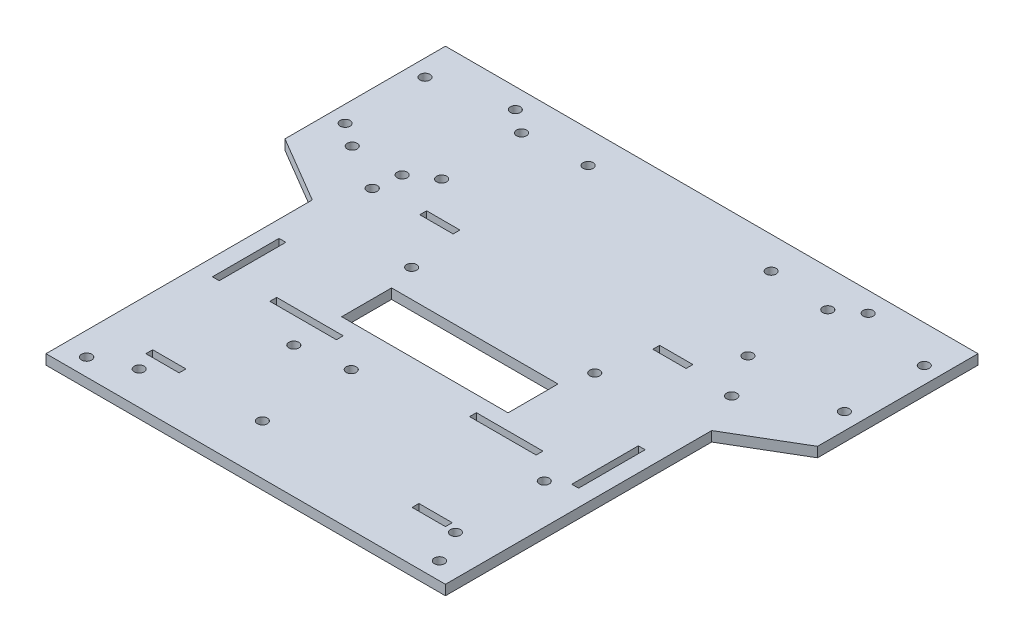
SolidWorks part; units mm, degrees
ref_plane "Front Plane" through (0, 0, 0) normal (0, 0, 1) x (1, 0, 0)
ref_plane "Top Plane" through (0, 0, 0) normal (0, 1, 0) x (1, 0, 0)
ref_plane "Right Plane" through (0, 0, 0) normal (1, 0, 0) x (0, 0, -1)
sketch "Sketch1" plane through (0, 0, 0) normal (0, 1, 0) x (1, 0, 0)
  line L0 (-60, 10) -> (-80, 21.7918)
  line L1 (60, -70) -> (-60, -70)
  line L2 (60, -70) -> (60, 70)
  line L3 (60, 70) -> (-60, 70)
  line L4 (-60, -70) -> (-60, 70)
  line L5 (60, -70) -> (-60, 70) construction
  line L6 (60, 70) -> (-60, -70) construction
  line L7 (-80, 21.7918) -> (-80, 70)
  line L8 (-80, 70) -> (-60, 70)
  line L9 (0, 0) -> (0, 70) construction
  line L10 (60, 10) -> (80, 21.7918)
  line L11 (80, 70) -> (60, 70)
  line L12 (80, 21.7918) -> (80, 70)
  point P0 (0, 0)
  dimension "D1" = 140
  dimension "D2" = 120
  dimension "D3" = 20
  dimension "D4" = 30.523
  dimension "D5" = 60
extrude "Boss-Extrude1" add sketch "Sketch1" along normal blind 3 contours L4 L1 L2 L3 | L8 L7 L0 L4 | L10 L12 L11 L2
sketch "Sketch2" plane through (0, 3, 0) normal (0, 1, 0) x (1, 0, 0)
  line L0 (60, -70) -> (60, 10) construction
  line L1 (-60, -70) -> (-60, 10) construction
  line L3 (60, -70) -> (-60, -70) construction
  circle A0 centre (-42, -60) radius 1.5
  circle A1 centre (-25, -30.5551) radius 1.5
  circle A2 centre (-10, -55) radius 1.5
  circle A3 centre (48, -55) radius 1.5
  circle A4 centre (-10, -28.3) radius 1.5
  circle A5 centre (48, -28.3) radius 1.5
  dimension "D1" = 3
  dimension "D2" = 34
  dimension "D3" = 10
  dimension "D4" = 3
  dimension "D6" = 3
  dimension "D9" = 15
  dimension "D7" = 3
  dimension "D11" = 12
  dimension "D12" = 3
  dimension "D13" = 3
  dimension "D5" = 17
  dimension "D8" = 58
  dimension "D10" = 15
  dimension "D14" = 26.7
  dimension "D15" = 26.7
  dimension "D16" = 58
  dimension "D17" = 12
  dimension "D18" = 18
extrude "Cut-Extrude1" cut sketch "Sketch2" against normal through all
sketch "Sketch3" plane through (0, 3, 0) normal (0, 1, 0) x (1, 0, 0)
  line L0 (-0.0296, 57.8856) -> (-0.0296, -0.1144) construction
  line L1 (-30.0296, 33.8856) -> (29.9704, 33.8856) construction
  line L4 (-80, 21.7918) -> (-80, 70) construction
  line L6 (-80, 21.7918) -> (-80, 70) construction
  line L7 (80, 70) -> (-80, 70) construction
  line L8 (-60, 10) -> (-60, 70) construction
  line L9 (60, 10) -> (60, 70) construction
  circle A0 centre (-27.5296, 60.3856) radius 1.5
  circle A1 centre (-27.5296, 7.3856) radius 1.5
  circle A2 centre (27.4704, 7.3856) radius 1.5
  circle A3 centre (27.4704, 60.3856) radius 1.5
  point P16 (-80, 45.8959)
  dimension "D1" = 52.4704
  dimension "D2" = 36.1144
  dimension "D3" = 3
  dimension "D4" = 79.9704
  dimension "D5" = 26.5
extrude "Cut-Extrude3" cut sketch "Sketch3" against normal through all
sketch "Sketch4" plane through (0, 3, 0) normal (0, 1, 0) x (1, 0, 0)
  line L0 (-60.5, 58.8639) -> (-60.5, 32.8639) construction
  line L1 (-80, 21.7918) -> (-80, 70) construction
  line L2 (80, 70) -> (-80, 70) construction
  line L3 (0, 0) -> (0, 70) construction
  circle A0 centre (-75, 34.8639) radius 1.5
  circle A1 centre (-75, 58.8639) radius 1.5
  circle A2 centre (-46, 34.8639) radius 1.5
  circle A3 centre (-46, 58.8639) radius 1.5
  circle A4 centre (46, 58.8639) radius 1.5
  circle A5 centre (46, 34.8639) radius 1.5
  circle A6 centre (75, 34.8639) radius 1.5
  circle A7 centre (75, 58.8639) radius 1.5
  dimension "D1" = 3
  dimension "D2" = 3
  dimension "D5" = 5
  dimension "D6" = 11.1361
  dimension "D7" = 5
  dimension "D3" = 24
  dimension "D4" = 14.5
extrude "Cut-Extrude4" cut sketch "Sketch4" against normal through all
sketch "Sketch5" plane through (0, 3, 0) normal (0, 1, 0) x (1, 0, 0)
  line L0 (80, 70) -> (-80, 70) construction
  line L1 (-80, 21.7918) -> (-80, 70) construction
  circle A0 centre (-68, 30) radius 1.5
  circle A1 centre (-53, 30) radius 1.5
  dimension "D1" = 3
  dimension "D2" = 3
  dimension "D3" = 40
  dimension "D4" = 40
  dimension "D6" = 12
  dimension "D5" = 15
extrude "Cut-Extrude5" cut sketch "Sketch5" against normal blind 3
sketch "Sketch6" plane through (0, 3, 0) normal (0, 1, 0) x (1, 0, 0)
  line L0 (60, -70) -> (-60, -70) construction
  line L1 (-45, -52.95) -> (-35, -52.95)
  line L2 (-45, -52.95) -> (-45, -55)
  line L3 (-45, -55) -> (-35, -55)
  line L4 (-35, -52.95) -> (-35, -55)
  line L5 (-45, -52.95) -> (-35, -55) construction
  line L6 (-45, -55) -> (-35, -52.95) construction
  line L7 (-60, -70) -> (-60, 10) construction
  line L8 (0, 0) -> (0, -70) construction
  line L9 (35, -52.95) -> (35, -55)
  line L10 (45, -55) -> (35, -55)
  line L11 (45, -52.95) -> (45, -55)
  line L12 (45, -52.95) -> (35, -52.95)
  line L13 (20, -22.75) -> (20, -20.7)
  line L14 (-20, -22.75) -> (-40, -22.75)
  line L15 (-20, -22.75) -> (-20, -20.7)
  line L16 (-20, -20.7) -> (-40, -20.7)
  line L17 (-40, -22.75) -> (-40, -20.7)
  line L18 (-20, -22.75) -> (-40, -20.7) construction
  line L19 (-20, -20.7) -> (-40, -22.75) construction
  line L20 (20, -22.75) -> (40, -22.75)
  line L21 (40, -22.75) -> (40, -20.7)
  line L22 (20, -20.7) -> (40, -20.7)
  line L23 (-60, -30) -> (60, -30) construction
  line L24 (60, -70) -> (60, 10) construction
  line L25 (-30, -21.725) -> (60, -21.725) construction
  line L26 (30, 24.35) -> (30, 22.3)
  line L27 (-40, 24.35) -> (-30, 24.35)
  line L28 (-40, 24.35) -> (-40, 22.3)
  line L29 (-40, 22.3) -> (-30, 22.3)
  line L30 (-30, 24.35) -> (-30, 22.3)
  line L31 (-40, 24.35) -> (-30, 22.3) construction
  line L32 (-40, 22.3) -> (-30, 24.35) construction
  line L33 (40, 24.35) -> (40, 22.3)
  line L34 (40, 24.35) -> (30, 24.35)
  line L35 (40, 22.3) -> (30, 22.3)
  circle A0 centre (-53, -64.8) radius 1.525
  circle A1 centre (53, -64.8) radius 1.525
  point P0 (-40, -53.975)
  point P16 (-30, -21.725)
  point P31 (-35, 23.325)
  dimension "D9" = 7
  dimension "D11" = 3.05
  dimension "D1" = 2.05
  dimension "D2" = 15
  dimension "D3" = 15
  dimension "D4" = 10
  dimension "D5" = 2.05
  dimension "D6" = 30.2
  dimension "D7" = 20
  dimension "D8" = 20
  dimension "D10" = 5.2
  dimension "D12" = 10
  dimension "D13" = 5
  dimension "D14" = 2.05
  dimension "D15" = 43
extrude "Cut-Extrude7" cut sketch "Sketch6" against normal through all
sketch "Sketch9" plane through (0, 3, 0) normal (0, 1, 0) x (1, 0, 0)
  line L0 (80, 70) -> (-80, 70) construction
  line L1 (-80, 21.7918) -> (-80, 70) construction
  line L2 (0, 0) -> (0, 70) construction
  circle A0 centre (-54, 22) radius 1.525
  circle A2 centre (54, 22) radius 1.525
  dimension "D1" = 3.05
  dimension "D2" = 48
  dimension "D3" = 26
extrude "Cut-Extrude8" cut sketch "Sketch9" against normal blind 3
sketch "Sketch10" plane through (0, 3, 0) normal (0, 1, 0) x (1, 0, 0)
  line L0 (60, -70) -> (60, 10) construction
  line L1 (24.8, -15.9751) -> (-25.2, -15.9751)
  line L2 (24.8, -15.9751) -> (24.8, -0.9751)
  line L3 (24.8, -0.9751) -> (-25.2, -0.9751)
  line L4 (-25.2, -15.9751) -> (-25.2, -0.9751)
  line L5 (24.8, -15.9751) -> (-25.2, -0.9751) construction
  line L6 (24.8, -0.9751) -> (-25.2, -15.9751) construction
  line L7 (80, 70) -> (-80, 70) construction
  point P0 (-0.2, -8.4751)
  dimension "D1" = 15
  dimension "D2" = 50
  dimension "D3" = 35.2
  dimension "D4" = 70.9751
extrude "Cut-Extrude9" cut sketch "Sketch10" against normal blind 5
sketch "Sketch11" plane through (0, 3, 0) normal (0, 1, 0) x (1, 0, 0)
  line L0 (80, 70) -> (-80, 70) construction
  line L1 (0, 0) -> (0, 70) construction
  line L2 (-80, 21.7918) -> (-80, 70) construction
  circle A0 centre (-53, 64) radius 1.5
  circle A1 centre (53, 64) radius 1.5
  dimension "D1" = 3
  dimension "D3" = 27
  dimension "D2" = 6
extrude "Cut-Extrude10" cut sketch "Sketch11" against normal blind 5
sketch "Sketch12" plane through (0, 3, 0) normal (0, 1, 0) x (1, 0, 0)
  line L0 (80, 70) -> (-80, 70) construction
  line L1 (-55, -5) -> (-52.95, -5)
  line L2 (-55, -5) -> (-55, -25)
  line L3 (-55, -25) -> (-52.95, -25)
  line L4 (-52.95, -5) -> (-52.95, -25)
  line L5 (-55, -5) -> (-52.95, -25) construction
  line L6 (-55, -25) -> (-52.95, -5) construction
  line L13 (-60, -70) -> (-60, 10) construction
  line L14 (60, -70) -> (-60, -70) construction
  line L15 (0, 0) -> (0, -70) construction
  line L20 (52.95, -5) -> (52.95, -25)
  line L21 (55, -25) -> (52.95, -25)
  line L22 (55, -5) -> (55, -25)
  line L23 (55, -5) -> (52.95, -5)
  point P0 (-53.975, -15)
  dimension "D1" = 20
  dimension "D2" = 75
  dimension "D3" = 2.05
  dimension "D4" = 5
extrude "Cut-Extrude11" cut sketch "Sketch12" against normal blind 10
